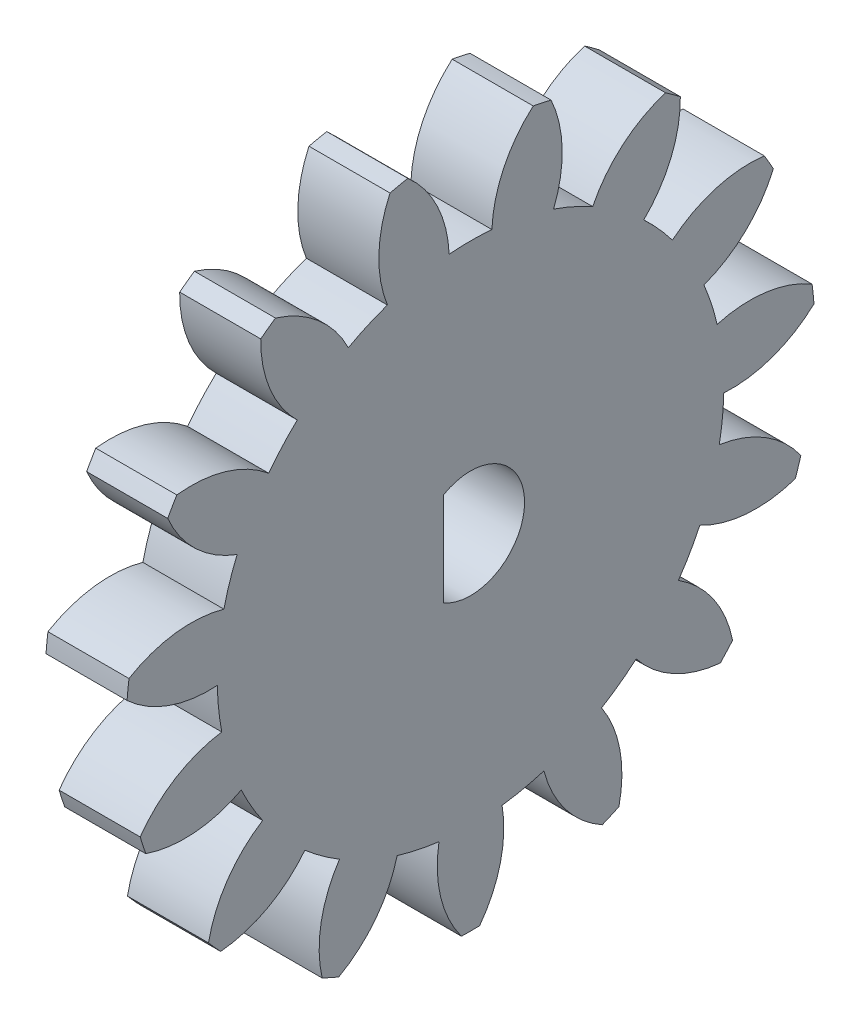
SolidWorks part; units mm, degrees
ref_plane "Plane1" through (0, 0, 0) normal (0, 0, 1) x (1, 0, 0)
ref_plane "Plane2" through (0, 0, 0) normal (0, 1, 0) x (1, 0, 0)
ref_plane "Plane3" through (0, 0, 0) normal (1, 0, 0) x (0, 0, -1)
sketch "HoldingSke" plane through (0, 0, 0) normal (0, 1, 0) x (1, 0, 0)
  line L0 (0, 0) -> (0.644, -0.1725)
  line L1 (-15, 0) -> (100, 0) construction
  line L2 (0, 0) -> (-2.1039, 2.3779)
  line L3 (0, 0) -> (-11.863, 4.5341)
  line L4 (0, 0) -> (8.3417, 2.2352)
  line L5 (0, 0) -> (-46.8476, -17.4728)
  line L6 (0, 0) -> (-2.4869, -1.6779)
  line L7 (-2.1039, 2.3779) -> (8.6586, 51.2059)
  line L8 (-76.2, 54.61) -> (-75.5, 54.61)
  line L9 (-71.009, 38.7566) -> (-53.1078, 45.2721)
  line L10 (-76.2, 71.12) -> (104.1128, 71.12)
  line L11 (0, 0) -> (-3, 0)
  line L12 (-76.2, 101.6) -> (-76.147, 101.6)
  line L13 (24.9733, 27.94) -> (52.9518, 28.4284)
  line L14 (24.9733, 27.94) -> (24.9743, 27.94)
  line L15 (24.9733, 27.94) -> (100.4006, 29.5858)
  line L16 (-63.627, -1.5) -> (-12.827, -1.5)
  circle A0 centre (0, 0) radius 2
  circle A1 centre (0, 0) radius 9.374
  circle A2 centre (0, 0) radius 37.5
  circle A3 centre (0, 0) radius 2
  dimension "MHD" = 18.748
  dimension "Hub_dia" = 75
  dimension "Bore" = 4
  dimension "MBD" = 4
  dimension "Num_teeth" = 15
  dimension "Pitch" = 0.6667
  dimension "Overall_len" = 50
  dimension "Show_teeth" = 15
  dimension "Thickness" = 3
  dimension "OAL" = 50.0001
  dimension "T_dim" = 0.7
  dimension "Ap" = 20
  dimension "H" = 19.05
  dimension "Pitch_radius" = 180.3128
  dimension "Width" = 3
  dimension "Backlash" = 0.053
  dimension "Addendum_fac" = 1
  dimension "Dedendum_fac" = 1.25
  dimension "Clearance_fac" = 0.25
  dimension "Dedendum_add" = 0.001
  dimension "Module" = 1.5
sketch "BasProSke" plane through (0, 0, 0) normal (0, 1, 0) x (1, 0, 0)
  line L0 (-10, 0) -> (60, 0) construction
  line L1 (0, 0) -> (0, 12.75)
  line L2 (0, 0) -> (3, 0)
  line L3 (3, 0) -> (3, 12.75)
  line L4 (3, 12.75) -> (0, 12.75)
  dimension "Thickness" = 3
  dimension "Diameter" = 25.5
revolve "Base-Revolve" add sketch "BasProSke" angle 360 about L0
sketch "TooCutSke" plane through (0, 0, 0) normal (1, 0, 0) x (0, 0, -1)
  line L1 (0, 0) -> (0, 107) construction
  line L2 (0, 0) -> (-1.2686, 11.1782) construction
  line L3 (0, 0) -> (-4.6563, 21.9061) construction
  line L4 (-1.2686, 11.1782) -> (-2.3281, 10.953) construction
  arc A0 (0.7915, 9.3405) -> (-0.7915, 9.3405) centre (0, 0) ccw
  arc A1 (2.3447, 12.5584) -> (-2.3447, 12.5584) centre (0, 0) ccw
  circle A2 centre (0, 0) radius 11.25 construction
  circle A3 centre (0, 0) radius 10.5715 construction
  arc A4 (-0.7915, 9.3405) -> (-2.3447, 12.5584) centre (-5.2877, 9.1541) ccw
  arc A5 (2.3447, 12.5584) -> (0.7915, 9.3405) centre (5.2877, 9.1541) ccw
  dimension "Root_dia" = 18.748
  dimension "Overcut_dia" = 25.5508
  dimension "Pitch_dia" = 22.5
  dimension "Base_dia" = 21.1431
  dimension "Flank_rad" = 4.5
  dimension "Half_ang" = 12
  dimension "Half_CT" = 1.0832
extrude "ToothCut" cut sketch "TooCutSke" along normal through all
fillet "Breaks" [suppressed] radius 0.03
fillet "RootFillets" [suppressed] radius 0.376
pattern_circular "TeethCuts" count 15 every 24 about axis through (-10, 0, 0) along (1, 0, 0) of "ToothCut", "RootFillets", "Breaks"
sketch "HubNeaOneSke" plane through (0, 0, 0) normal (-1, 0, 0) x (0, 0, 1)
  circle A0 centre (0, 0) radius 9.374
  dimension "Diameter" = 18.748
extrude "HubNearOne" [suppressed] add sketch "HubNeaOneSke" along normal blind 47.0001
sketch "HubNeaBotSke" plane through (0, 0, 0) normal (-1, 0, 0) x (0, 0, 1)
  circle A0 centre (0, 0) radius 9.374
  dimension "Diameter" = 18.748
extrude "HubNearBoth" [suppressed] add sketch "HubNeaBotSke" along normal blind 23.5
ref_plane "FarPln" through (3, 0, 0) normal (1, 0, 0) x (0, 0, -1)
sketch "HubFarSke" plane through (3, 0, 0) normal (1, 0, 0) x (0, 0, -1)
  circle A0 centre (0, 0) radius 9.374
  dimension "Diameter" = 18.748
extrude "HubFar" [suppressed] add sketch "HubFarSke" along normal blind 23.5
sketch "BorSke" plane through (0, 0, 0) normal (1, 0, 0) x (0, 0, -1)
  circle A0 centre (0, 0) radius 2
  dimension "Diameter" = 4
extrude "Bore" cut sketch "BorSke" along normal mid plane 100.0001
sketch "KeySke" plane through (0, 0, 0) normal (1, 0, 0) x (0, 0, -1)
  line L0 (-0.8, 0) -> (-0.8, 2.7)
  line L1 (-0.8, 2.7) -> (0.8, 2.7)
  line L2 (0.8, 2.7) -> (0.8, 0)
  line L3 (0, 0) -> (0, 34) construction
  line L4 (-0.8, 0) -> (0.8, 0)
  dimension "Offset" = 2.7
  dimension "Width" = 1.6
extrude "Keyway" [suppressed] cut sketch "KeySke" along normal mid plane 100.0001
pattern_circular "Keyway2" [suppressed] count 2 every 90 about axis through (-10, 0, 0) along (1, 0, 0)
sketch "Esquisse1" plane through (0, 0, 0) normal (-1, 0, 0) x (0, 0, 1)
  line L0 (0, 0) -> (0, 4.3875) construction
  line L1 (0, 0) -> (5.3155, 0) construction
  line L2 (1, 1.7321) -> (1, -1.7321)
  circle A0 centre (0, 0) radius 2 construction
  arc A1 (1, -1.7321) -> (1, 1.7321) centre (0, 0) ccw
  dimension "D1" = 1
extrude "Boss.-Extru.1" add sketch "Esquisse1" against normal blind 3
equation "' \"Module@HoldingSke\" = 6.35"
equation "' \"Num_teeth@HoldingSke\" = 12"
equation "' \"Ap@HoldingSke\" =  20"
equation "' \"Ap@HoldingSke\" = 20"
equation "' \"Width@HoldingSke\" = 0.5 * 25.4"
equation "' \"Hub_dia@HoldingSke\"= 1 * 25.4"
equation "' \"Hub_dia@HoldingSke\" = 1 * 25.4"
equation "' \"Overall_len@HoldingSke\" = 1.0 * 25.4"
equation "' \"Bore@HoldingSke\" = 0.75 * 25.4"
equation "' \"T_dim@HoldingSke\" = 0.1 * 25.4"
equation "' \"Width@KeySke\" = 0.25 * 25.4"
equation "' \"Show_teeth@HoldingSke\" = 13"
equation "' \"Backlash@HoldingSke\" = 0.009 * 25.4"
equation "' \"Addendum_fac@HoldingSke\" = 1.0"
equation "' \"Dedendum_fac@HoldingSke\" = 1.25"
equation "' \"Dedendum_add@HoldingSke\" = 0.00005 * 25.4"
equation "' \"Clearance_fac@HoldingSke\" = 0.25"
equation "\"Pitch@HoldingSke\" = 1 / \"Module@HoldingSke\""
equation "\"Overcut_dia@TooCutSke\" = (\"Num_teeth@HoldingSke\" + 2 * \"Addendum_fac@HoldingSke\") / \"Pitch@HoldingSke\" + 0.002 * 25.4"
equation "\"Pitch_dia@TooCutSke\" = \"Num_teeth@HoldingSke\" / \"Pitch@HoldingSke\""
equation "\"Base_dia@TooCutSke\" = \"Num_teeth@HoldingSke\" / \"Pitch@HoldingSke\" * cos((\"Ap@HoldingSke\"  * 3.14159265 / 180))"
equation "\"Root_dia@TooCutSke\" = (\"Num_teeth@HoldingSke\" + 2) / \"Pitch@HoldingSke\" - 2 * (\"Addendum_fac@HoldingSke\" + \"Dedendum_fac@HoldingSke\") / \"Pitch@HoldingSke\" - \"Dedendum_add@HoldingSke\" * 2"
equation "\"Half_ang@TooCutSke\" = 180 / \"Num_teeth@HoldingSke\""
equation "\"Half_CT@TooCutSke\" = \"Num_teeth@HoldingSke\" / \"Pitch@HoldingSke\" * sin((3.14159265 / 2 / \"Num_teeth@HoldingSke\")) / 2 - 7 * \"Backlash@HoldingSke\" / 4"
equation "\"Flank_rad@TooCutSke\" = \"Num_teeth@HoldingSke\" / \"Pitch@HoldingSke\" / 5"
equation "\"Radius@RootFillets\" = \"Clearance_fac@HoldingSke\" / \"Pitch@HoldingSke\" + \"Dedendum_add@HoldingSke\""
equation "\"Break_rad@Breaks\" = 0.02 / \"Pitch@HoldingSke\""
equation "\"Thickness@HoldingSke\" = \"Width@HoldingSke\""
equation "\"OAL@HoldingSke\" = \"Thickness@HoldingSke\""
equation "\"MHD@HoldingSke\" = (\"Num_teeth@HoldingSke\" + 2) / \"Pitch@HoldingSke\" - 2 * (\"Addendum_fac@HoldingSke\" + \"Dedendum_fac@HoldingSke\")  / \"Pitch@HoldingSke\" - \"Dedendum_add@HoldingSke\" * 2"
equation "\"MBD@HoldingSke\" = (\"Num_teeth@HoldingSke\" + 2) / \"Pitch@HoldingSke\" - 2 * (\"Addendum_fac@HoldingSke\" + \"Dedendum_fac@HoldingSke\")  / \"Pitch@HoldingSke\" - \"Dedendum_add@HoldingSke\" * 2 - 0.002 * 25.4"
equation "\"MHD@HoldingSke\" = ((sgn( \"MHD@HoldingSke\" - \"Hub_dia@HoldingSke\" )-1)*( \"MHD@HoldingSke\" - \"Hub_dia@HoldingSke\" ))/-2+ \"Hub_dia@HoldingSke\""
equation "\"MBD@HoldingSke\" = ((sgn( \"MBD@HoldingSke\" - \"Bore@HoldingSke\" )-1)*( \"MBD@HoldingSke\" - \"Bore@HoldingSke\" ))/-2+ \"Bore@HoldingSke\""
equation "\"OAL@HoldingSke\" = ((sgn( \"OAL@HoldingSke\" - \"Overall_len@HoldingSke\" )+1)*( \"OAL@HoldingSke\" - \"Overall_len@HoldingSke\" ))/2 + \"Overall_len@HoldingSke\" + 0.000002 * 25.4"
equation "\"Num_teeth@TeethCuts\" = int( \"Show_teeth@HoldingSke\" ) + 1"
equation "\"Num_teeth@TeethCuts\" = ((sgn( \"Num_teeth@TeethCuts\" - \"Num_teeth@HoldingSke\" )-1)*( \"Num_teeth@TeethCuts\" - \"Num_teeth@HoldingSke\" ))/-2+ \"Num_teeth@HoldingSke\""
equation "\"Num_teeth@TeethCuts\" = ((sgn( \"Num_teeth@TeethCuts\" - 2.0)+1)*( \"Num_teeth@TeethCuts\" - 2.0))/2 +2.0"
equation "\"Angle@TeethCuts\" = 360.0 / \"Num_teeth@HoldingSke\""
equation "\"Diameter@BasProSke\" = (\"Num_teeth@HoldingSke\" + 2 * \"Addendum_fac@HoldingSke\") / \"Pitch@HoldingSke\""
equation "\"Thickness@BasProSke\"  = \"Thickness@HoldingSke\""
equation "' \"Fillet_rad@BasProSke\" =  \"Thickness@HoldingSke\" * 0.05"
equation "' \"Fillet_rad@BasProSke\" = \"Thickness@HoldingSke\" * 0.05"
equation "\"MHD@HoldingSke\" = ((sgn( \"MHD@HoldingSke\" - \"Root_dia@TooCutSke\" )-1)*( \"MHD@HoldingSke\" - \"Root_dia@TooCutSke\" ))/-2+ \"Root_dia@TooCutSke\""
equation "\"Diameter@HubNeaOneSke\" = \"MHD@HoldingSke\""
equation "\"Length@HubNearOne\" = \"OAL@HoldingSke\" - \"Thickness@BasProSke\""
equation "\"Diameter@HubNeaBotSke\" = \"MHD@HoldingSke\""
equation "\"Length@HubNearBoth\" = ( \"OAL@HoldingSke\" - \"Thickness@BasProSke\" ) / 2.0"
equation "\"Thickness@FarPln\" = \"Thickness@BasProSke\""
equation "\"Diameter@HubFarSke\" = \"MHD@HoldingSke\""
equation "\"Length@HubFar\" = ( \"OAL@HoldingSke\" - \"Thickness@BasProSke\" ) / 2.0"
equation "\"Diameter@BorSke\" = \"MBD@HoldingSke\""
equation "\"D1@Bore\" = \"OAL@HoldingSke\" * 2.0"
equation "\"D1@Keyway\" = \"OAL@HoldingSke\" * 2.0"
equation "\"Offset@KeySke\" = \"T_dim@HoldingSke\" + \"MBD@HoldingSke\" / 2.0"
